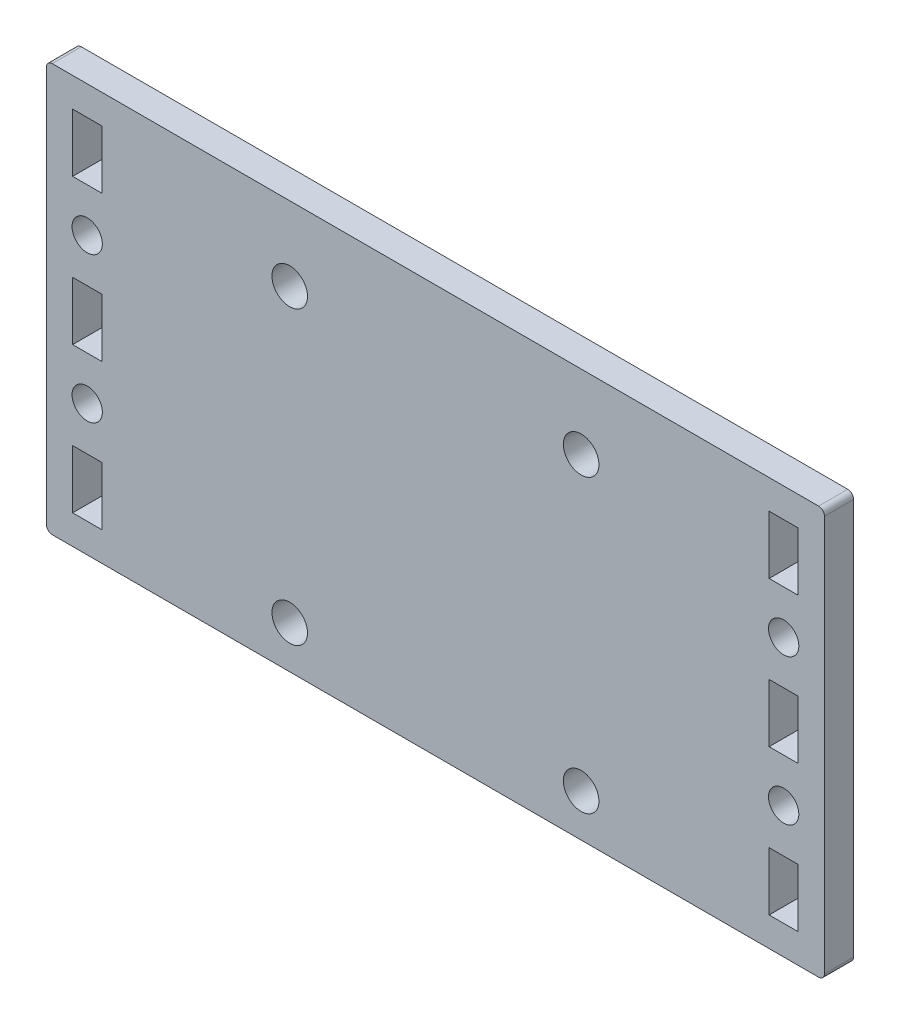
SolidWorks part; units mm, degrees
material "6061 Alloy"
ref_plane "Front Plane" through (0, 0, 0) normal (0, 0, 1) x (1, 0, 0)
ref_plane "Top Plane" through (0, 0, 0) normal (0, 1, 0) x (1, 0, 0)
ref_plane "Right Plane" through (0, 0, 0) normal (1, 0, 0) x (0, 0, -1)
sketch "Sketch1" plane through (0, 0, 0) normal (0, 0, 1) x (1, 0, 0)
  line L0 (0, 27.5) -> (0, -12.55) construction
  line L1 (-66.75, 35) -> (66.75, 35)
  line L2 (-66.75, 35) -> (-66.75, -35)
  line L3 (-66.75, -35) -> (66.75, -35)
  line L4 (66.75, 35) -> (66.75, -35)
  line L5 (-66.75, 35) -> (66.75, -35) construction
  line L6 (-66.75, -35) -> (66.75, 35) construction
  line L7 (40.05, 27.5) -> (-40.05, 27.5) construction
  line L8 (40.05, 27.5) -> (40.05, -12.55) construction
  line L9 (40.05, -12.55) -> (-40.05, -12.55) construction
  line L10 (-40.05, 27.5) -> (-40.05, -12.55) construction
  line L11 (65.75, 27.5) -> (-65.75, 27.5) construction
  line L12 (-52.75, 35) -> (-52.75, -21) construction
  line L13 (-52.75, -21) -> (52.75, -21) construction
  line L14 (52.75, 35) -> (52.75, -21) construction
  line L15 (-66.75, -25) -> (-52.75, -25) construction
  line L16 (-62.25, -20) -> (-57.25, -20)
  line L17 (-62.25, -20) -> (-62.25, -30)
  line L18 (-62.25, -30) -> (-57.25, -30)
  line L19 (-57.25, -20) -> (-57.25, -30)
  line L20 (-62.25, -20) -> (-57.25, -30) construction
  line L21 (-62.25, -30) -> (-57.25, -20) construction
  line L22 (-59.75, -25) -> (-59.75, 0) construction
  line L23 (62.25, -30) -> (57.25, -30)
  line L24 (-62.25, 5) -> (-57.25, 5)
  line L25 (-62.25, 5) -> (-62.25, -5)
  line L26 (-62.25, -5) -> (-57.25, -5)
  line L27 (-57.25, 5) -> (-57.25, -5)
  line L28 (-62.25, 5) -> (-57.25, -5) construction
  line L29 (-62.25, -5) -> (-57.25, 5) construction
  line L30 (57.25, -20) -> (57.25, -30)
  line L31 (62.25, -20) -> (62.25, -30)
  line L32 (62.25, -20) -> (57.25, -20)
  line L33 (62.25, 5) -> (57.25, 5)
  line L34 (57.25, 5) -> (57.25, -5)
  line L35 (62.25, -5) -> (57.25, -5)
  line L36 (62.25, 5) -> (62.25, -5)
  line L37 (-62.25, 0) -> (-57.25, 0) construction
  line L38 (-66.75, 12.5) -> (-52.75, 12.5) construction
  line L39 (-62.25, 25) -> (-57.25, 25) construction
  line L40 (-62.25, 30) -> (-57.25, 20) construction
  line L41 (-62.25, 20) -> (-57.25, 30) construction
  line L42 (-57.25, 20) -> (-57.25, 30)
  line L43 (-62.25, 30) -> (-57.25, 30)
  line L44 (-62.25, 20) -> (-62.25, 30)
  line L45 (-62.25, 20) -> (-57.25, 20)
  line L46 (62.25, 20) -> (57.25, 30) construction
  line L47 (62.25, 30) -> (57.25, 20) construction
  line L48 (62.25, 25) -> (57.25, 25) construction
  line L49 (62.25, 20) -> (57.25, 20)
  line L50 (62.25, 20) -> (62.25, 30)
  line L51 (62.25, 30) -> (57.25, 30)
  line L52 (57.25, 20) -> (57.25, 30)
  circle A0 centre (25, 22.3) radius 3.05
  circle A1 centre (-25, 22.3) radius 3.05
  circle A2 centre (-59.75, -12.5) radius 2.6
  circle A3 centre (59.75, -12.5) radius 2.6
  circle A4 centre (-59.75, 12.5) radius 2.6
  circle A5 centre (59.75, 12.5) radius 2.6
  circle A6 centre (25, -27.7) radius 3.05
  circle A7 centre (-25, -27.7) radius 3.05
  point P0 (0, 0)
  point P12 (0, 27.5)
  point P23 (-59.75, -25)
  dimension "D5" = 12.7
  dimension "D6" = 6.1
  dimension "D7" = 25
  dimension "D13" = 5.2
  dimension "D15" = 50
  dimension "D2" = 133.5
  dimension "D3" = 80.1
  dimension "D4" = 40.05
  dimension "D8" = 14
  dimension "D9" = 5
  dimension "D10" = 5
  dimension "D11" = 10
  dimension "D12" = 35
  dimension "D14" = 5
extrude "Boss-Extrude1" add sketch "Sketch1" along normal blind 5
fillet "Fillet1" radius 1 4 edges at (66.75, 35, 2.5) (66.75, -35, 2.5) (-66.75, -35, 2.5) (-66.75, 35, 2.5)
ref_plane "Plane1" through (0, -25, 0) normal (0, 1, 0) x (1, 0, 0)
ref_plane "Plane2" through (0, 0, 0) normal (0, -1, 0) x (-1, 0, 0)
ref_plane "Plane3" through (0, 25, 0) normal (0, -1, 0) x (-1, 0, 0)
